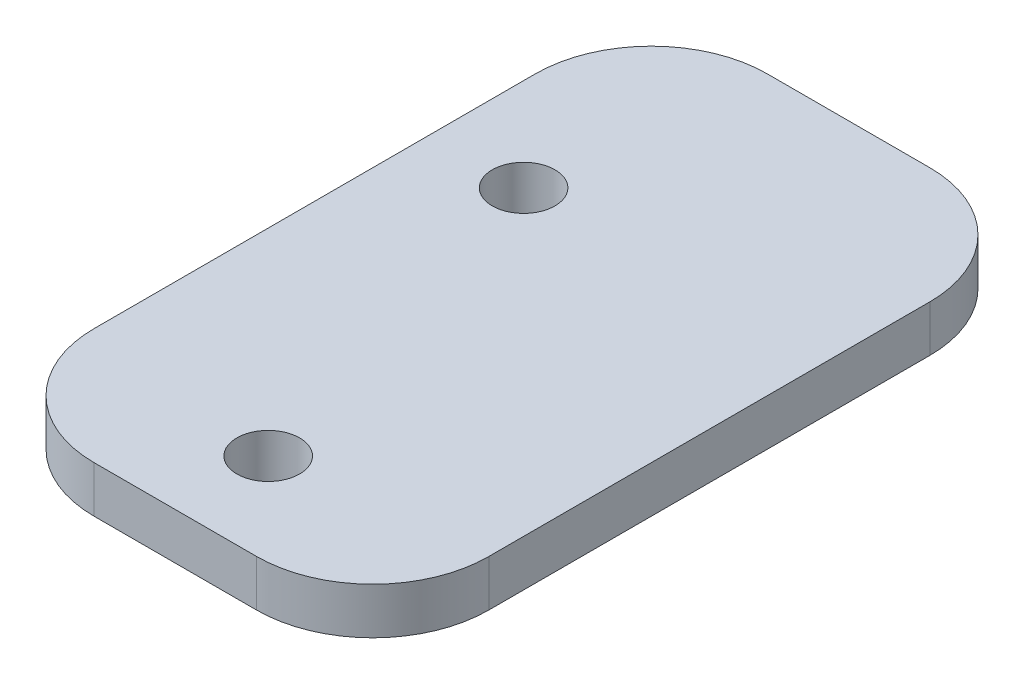
SolidWorks part; units mm, degrees
material "碳纤维"
ref_plane "前视基准面" through (0, 0, 0) normal (0, 0, 1) x (1, 0, 0)
ref_plane "上视基准面" through (0, 0, 0) normal (0, 1, 0) x (1, 0, 0)
ref_plane "右视基准面" through (0, 0, 0) normal (1, 0, 0) x (0, 0, -1)
sketch "草图1" plane through (0, 0, 0) normal (0, 1, 0) x (1, 0, 0)
  line L1 (-8.5, -14.5) -> (8.5, -14.5)
  line L2 (-8.5, -14.5) -> (-8.5, 14.5)
  line L3 (-8.5, 14.5) -> (8.5, 14.5)
  line L4 (8.5, -14.5) -> (8.5, 14.5)
  line L5 (0, 14.5) -> (0, -14.5) construction
  line L6 (-8.5, 0) -> (8.5, 0) construction
  circle A0 centre (0, -10.5) radius 1.35
  circle A1 centre (-4.5, 5) radius 1.35
  point P0 (0, 0)
  dimension "D6" = 2.7
  dimension "D1" = 17
  dimension "D2" = 29
  dimension "D3" = 4
  dimension "D4" = 4
  dimension "D5" = 19.5
extrude "凸台-拉伸1" add sketch "草图1" along normal blind 2
fillet "圆角1" radius 5 4 edges at (8.5, 1, 14.5) (-8.5, 1, -14.5) (8.5, 1, -14.5) (-8.5, 1, 14.5)
sketch "草图2" plane through (0, 2, 0) normal (0, 1, 0) x (1, 0, 0)
  circle A0 centre (-4.5, 5) radius 5.5
  circle A1 centre (-4.5, 5) radius 11
  dimension "D1" = 11
  dimension "D2" = 22
extrude "切除-拉伸1" [suppressed] cut sketch "草图2" against normal blind 1
fillet "圆角2" [suppressed] radius 2
